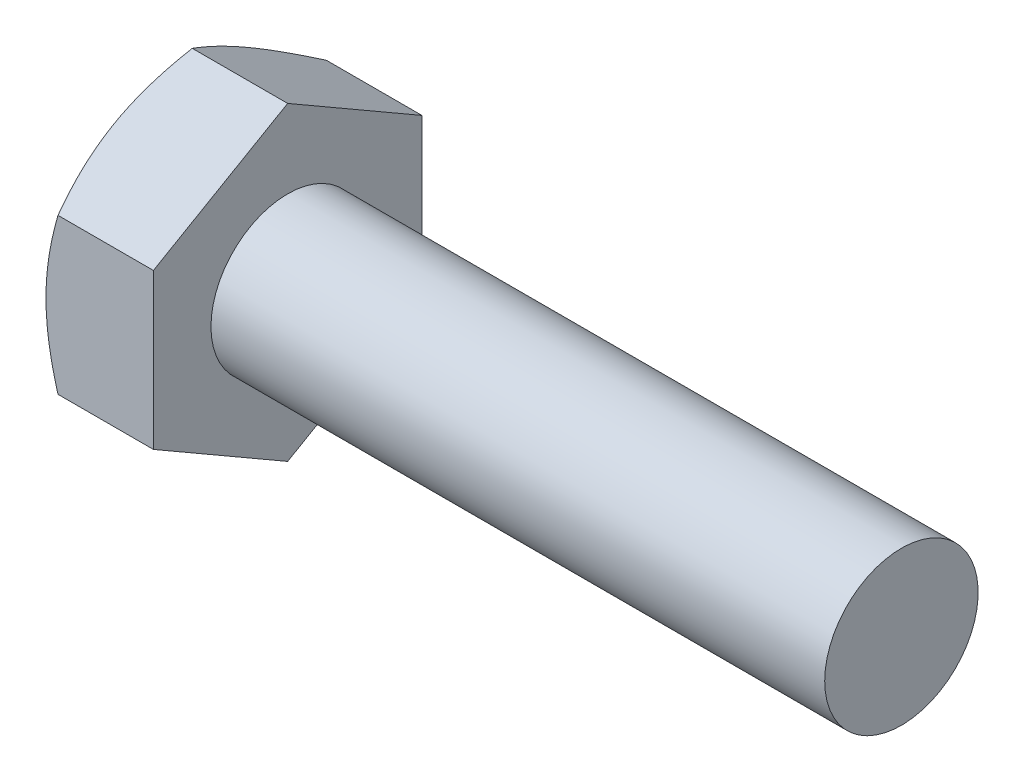
SolidWorks part; units mm, degrees
extrude "BaseHead" add sketch "Sketch1" along normal blind 2.8
sketch "Sketch1" plane through (0, 0, 0) normal (1, 0, 0) x (0, 0, -1)
  line L0 (3.5, 2.0207) -> (3.5, -2.0207)
  line L1 (-3.5, 2.0207) -> (-3.5, -2.0207)
  line L2 (3.5, -2.0207) -> (0, -4.0415)
  line L3 (0, -4.0415) -> (-3.5, -2.0207)
  line L4 (3.5, 2.0207) -> (0, 4.0415)
  line L5 (0, 4.0415) -> (-3.5, 2.0207)
  dimension "Width_flats" = 7
  dimension "D2" = 120
  dimension "D3" = 3.5
  dimension "D4" = 3.5
  dimension "D5" = 3.5
ref_plane "Plane1" through (0, 0, 0) normal (0, 0, 1) x (1, 0, 0)
ref_plane "Plane2" through (0, 0, 0) normal (0, 1, 0) x (1, 0, 0)
ref_plane "Plane3" through (0, 0, 0) normal (1, 0, 0) x (0, 0, -1)
sketch "BodySke" plane through (0, 0, 0) normal (0, 0, 1) x (1, 0, 0)
  line L0 (0, 2.0207) -> (0, -2.0207) construction
  line L1 (0, 0) -> (18.8, 0)
  line L2 (0, 0) -> (0, 2)
  line L3 (0, 2) -> (18.8, 2)
  line L4 (18.8, 0) -> (18.8, 2)
  line L5 (2.8, 4.0415) -> (2.8, 2.0207) construction
  line L7 (0, 0) -> (96.52, 0) construction
  line L10 (3.5, 15.24) -> (3.5, -1.27) construction
  line L11 (4.8, 15.24) -> (4.8, -1.27) construction
  line L12 (2.8, 2.0207) -> (2.8, -2.0207) construction
  dimension "Diameter" = 4
revolve "BaseBody" add sketch "BodySke" angle 360 about L7
cosmetic thread "ThreadCosmetic"
sketch "Sketch3" plane through (0, 0, 0) normal (0, 0, 1) x (1, 0, 0)
  line L0 (0, 3.5) -> (3.1994, 9.0415)
  line L1 (0, 4.0415) -> (0, 2.0207) construction
  line L2 (3.1994, 9.0415) -> (3.1994, 14.0415)
  line L3 (3.1994, 14.0415) -> (-10, 14.0415)
  line L4 (-10, 14.0415) -> (-10, 3.5)
  line L5 (-10, 3.5) -> (0, 3.5)
  line L6 (0, 0) -> (99.06, 0) construction
  line L7 (2.8, 4.0415) -> (0, 4.0415) construction
  dimension "D1" = 3.5
  dimension "D2" = 5
  dimension "D3" = 10
  dimension "D4" = 5
  dimension "Head_ch_ang" = 30
revolve "HeadChamfer" cut sketch "Sketch3" angle 360 about L6
sketch "SkeExt" plane through (0, 0, 0) normal (0, 0, 1) x (1, 0, 0)
  line L12 (2.8, 2.0207) -> (2.8, -2.0207) construction
  circle A0 centre (16.3, 0) radius 0.5
  dimension "D1" = 13.5
  dimension "D2" = 1
extrude "Cut-Extrude1" [suppressed] cut sketch "SkeExt" against normal through all and the other way through all
sketch "Sketch2" plane through (9.6236, 0.011, 3.5) normal (0, 0, 1) x (1, 0, 0)
  line L1 (-6.8236, -2.0318) -> (-6.8236, -4.0525) construction
  line L4 (-9.6236, -0.011) -> (86.8964, -0.011) construction
  circle A0 centre (-8.2236, -0.011) radius 0.5
  dimension "D1" = 1.4
  dimension "d2" = 1
extrude "Cut-Extrude2" [suppressed] cut sketch "Sketch2" against normal through all
pattern_circular "CirPattern1" [suppressed] count 2 every 60 about axis through (0, 0, 0) along (1, 0, 0)
sketch "Sketch5" plane through (0, -1.9845, 0.0659) normal (-1, 0, 0) x (0, 0, 1)
  circle A0 centre (-0.0659, 1.9845) radius 2.8
  dimension "D1" = 5.6
extrude "Cut-Extrude3" [suppressed] cut sketch "Sketch5" against normal blind 0.8
equation "\"D3@Sketch1\" = \"Width_flats@Sketch1\" / 2"
equation "\"D4@Sketch1\" = \"D3@Sketch1\""
equation "\"D5@Sketch1\" = \"D4@Sketch1\""
equation "\"D1@Sketch3\" = \"Width_flats@Sketch1\" / 2"
equation "\"Thread_length@ThreadCosmetic\" = ((sgn( (\"Length@BodySke\" - \"Advance@BodySke\" ) - \"Thread_nom@BodySke\" )-1)*( (\"Length@BodySke\" - \"Advance@BodySke\" ) - \"Thread_nom@BodySke\" ))/-2+ \"Thread_nom@BodySke\""
